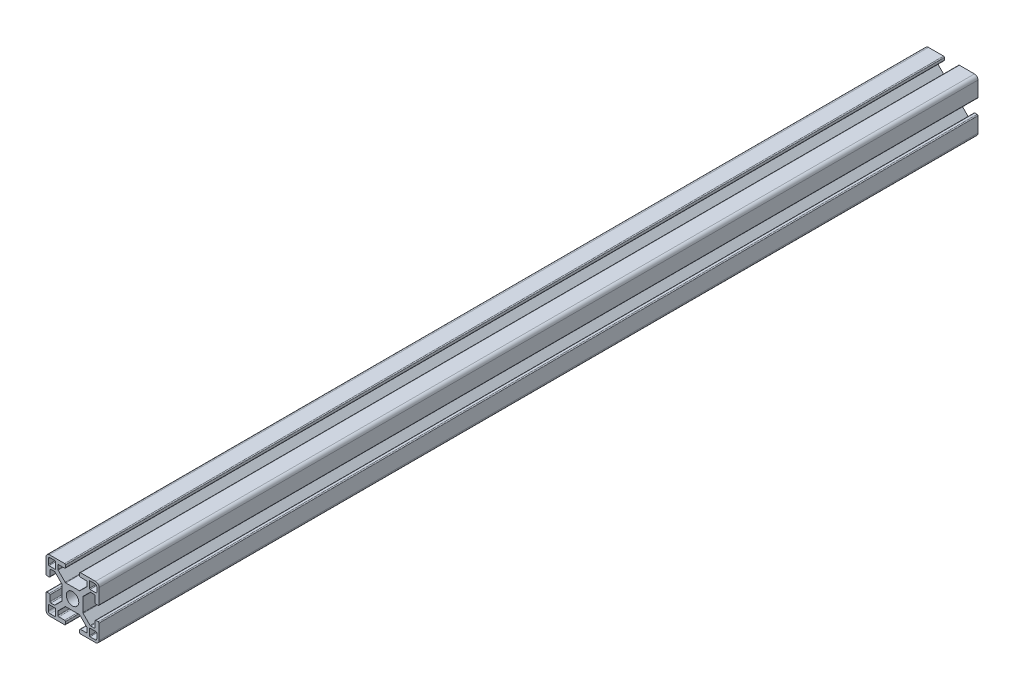
SolidWorks part; units mm, degrees
ref_plane "Front Plane" through (0, 0, 0) normal (0, 0, 1) x (1, 0, 0)
ref_plane "Top Plane" through (0, 0, 0) normal (0, 1, 0) x (1, 0, 0)
ref_plane "Right Plane" through (0, 0, 0) normal (1, 0, 0) x (0, 0, -1)
sketch "Sketch1" plane through (0, 0, 0) normal (0, 0, 1) x (1, 0, 0)
  line L0 (3.9799, -2.4733) -> (3.1981, -1.4942) construction
  line L1 (1.4942, -3.1981) -> (2.4733, -3.9799) construction
  line L2 (-2.4733, -3.9799) -> (-1.4942, -3.1981) construction
  line L3 (-3.1981, -1.4942) -> (-3.9799, -2.4733) construction
  line L4 (-3.9799, 2.4733) -> (-3.1981, 1.4942) construction
  line L5 (-1.4942, 3.1981) -> (-2.4733, 3.9799) construction
  line L6 (2.4733, 3.9799) -> (1.4942, 3.1981) construction
  line L7 (3.1981, 1.4942) -> (3.9799, 2.4733) construction
  line L8 (-12.6999, -13.6999) -> (-9.881, -13.6999)
  line L9 (-13.6999, -9.881) -> (-13.6999, -12.6999)
  line L10 (-9.88, -9.5) -> (-13.3189, -9.5)
  line L11 (-9.5, -13.3189) -> (-9.5, -9.88)
  line L12 (13.6999, -12.6999) -> (13.6999, -9.881)
  line L13 (9.881, -13.6999) -> (12.6999, -13.6999)
  line L14 (9.5, -9.88) -> (9.5, -13.3189)
  line L15 (13.3189, -9.5) -> (9.88, -9.5)
  line L16 (9.88, 9.5) -> (13.3189, 9.5)
  line L17 (9.5, 13.3189) -> (9.5, 9.88)
  line L18 (12.6999, 13.6999) -> (9.881, 13.6999)
  line L19 (13.6999, 9.881) -> (13.6999, 12.6999)
  line L20 (-13.6999, 12.6999) -> (-13.6999, 9.881)
  line L21 (-9.881, 13.6999) -> (-12.6999, 13.6999)
  line L22 (-9.5, 9.88) -> (-9.5, 13.3189)
  line L23 (-13.3189, 9.5) -> (-9.88, 9.5)
  line L24 (14.4999, -4) -> (13.2425, -4)
  line L25 (12.7425, -4.5) -> (12.7425, -7.7325)
  line L26 (12.2428, -8.25) -> (10.2602, -8.25)
  line L27 (9.9066, -8.1035) -> (5.9811, -4.178)
  line L28 (5.8347, -3.8245) -> (5.8347, -1.0125)
  line L29 (5.8347, -1.0125) -> (5.3247, -0.0625) construction
  line L30 (5.3247, -0.0625) -> (5.8347, 0.8875) construction
  line L31 (5.8347, 0.8875) -> (5.8347, 3.8245)
  line L32 (5.9811, 4.178) -> (9.9066, 8.1035)
  line L33 (10.2602, 8.25) -> (12.2428, 8.25)
  line L34 (12.7425, 7.7325) -> (12.7425, 4.5)
  line L35 (13.2425, 4) -> (14.4999, 4)
  line L36 (14.9999, 4.5) -> (14.9999, 12.9999)
  line L37 (12.9999, 14.9999) -> (4.5, 14.9999)
  line L38 (4, 14.4999) -> (4, 13.2425)
  line L39 (4.5, 12.7425) -> (7.7325, 12.7425)
  line L40 (8.25, 12.2428) -> (8.25, 10.2602)
  line L41 (8.1035, 9.9066) -> (4.178, 5.9811)
  line L42 (3.8245, 5.8347) -> (0.95, 5.8347)
  line L43 (0.95, 5.8347) -> (0, 5.3247) construction
  line L44 (0, 5.3247) -> (-0.95, 5.8347) construction
  line L45 (-0.95, 5.8347) -> (-3.8245, 5.8347)
  line L46 (-4.178, 5.9811) -> (-8.1035, 9.9066)
  line L47 (-8.25, 10.2602) -> (-8.25, 12.2428)
  line L48 (-7.7325, 12.7425) -> (-4.5, 12.7425)
  line L49 (-4, 13.2425) -> (-4, 14.4999)
  line L50 (-4.5, 14.9999) -> (-12.9999, 14.9999)
  line L51 (-14.9999, 12.9999) -> (-14.9999, 4.5)
  line L52 (-14.4999, 4) -> (-13.2425, 4)
  line L53 (-12.7425, 4.5) -> (-12.7425, 7.7325)
  line L54 (-12.2428, 8.25) -> (-10.2602, 8.25)
  line L55 (-9.9066, 8.1035) -> (-5.9811, 4.178)
  line L56 (-5.8347, 3.8245) -> (-5.8347, 0.8875)
  line L57 (-5.8347, 0.8875) -> (-5.3247, -0.0625) construction
  line L58 (-5.3247, -0.0625) -> (-5.8347, -1.0125) construction
  line L59 (-5.8347, -1.0125) -> (-5.8347, -3.8245)
  line L60 (-5.9811, -4.178) -> (-9.9066, -8.1035)
  line L61 (-10.2602, -8.25) -> (-12.2428, -8.25)
  line L62 (-12.7425, -7.7325) -> (-12.7425, -4.5)
  line L63 (-13.2425, -4) -> (-14.4999, -4)
  line L64 (-14.9999, -4.5) -> (-14.9999, -12.9999)
  line L65 (-12.9999, -14.9999) -> (-4.5, -14.9999)
  line L66 (-4, -14.4999) -> (-4, -13.2425)
  line L67 (-4.5, -12.7425) -> (-7.7325, -12.7425)
  line L68 (-8.25, -12.2428) -> (-8.25, -10.2602)
  line L69 (-8.1035, -9.9066) -> (-4.178, -5.9811)
  line L70 (-3.8245, -5.8347) -> (-0.95, -5.8347)
  line L71 (-0.95, -5.8347) -> (0, -5.3247) construction
  line L72 (0, -5.3247) -> (0.95, -5.8347) construction
  line L73 (0.95, -5.8347) -> (3.8245, -5.8347)
  line L74 (4.178, -5.9811) -> (8.1035, -9.9066)
  line L75 (8.25, -10.2602) -> (8.25, -12.2428)
  line L76 (7.7325, -12.7425) -> (4.5, -12.7425)
  line L77 (4, -13.2425) -> (4, -14.4999)
  line L78 (4.5, -14.9999) -> (12.9999, -14.9999)
  line L79 (14.9999, -12.9999) -> (14.9999, -4.5)
  line L80 (-5.8347, -1.0125) -> (-5.8347, 0.8875)
  line L81 (-0.95, 5.8347) -> (0.95, 5.8347)
  line L82 (5.8347, 0.8875) -> (5.8347, -1.0125)
  line L83 (-0.95, -5.8347) -> (0.95, -5.8347)
  arc A0 (2.4733, -3.9799) -> (3.9799, -2.4733) centre (3.1422, -3.1422) ccw construction
  arc A1 (-1.4942, -3.1981) -> (1.4942, -3.1981) centre (0, 0) ccw construction
  arc A2 (-3.9799, -2.4733) -> (-2.4733, -3.9799) centre (-3.1422, -3.1422) ccw construction
  arc A3 (-3.1981, 1.4942) -> (-3.1981, -1.4942) centre (0, 0) ccw construction
  arc A4 (-2.4733, 3.9799) -> (-3.9799, 2.4733) centre (-3.1422, 3.1422) ccw construction
  arc A5 (1.4942, 3.1981) -> (-1.4942, 3.1981) centre (0, 0) ccw construction
  arc A6 (3.9799, 2.4733) -> (2.4733, 3.9799) centre (3.1422, 3.1422) ccw construction
  arc A7 (3.1981, -1.4942) -> (3.1981, 1.4942) centre (0, 0) ccw construction
  arc A8 (-13.6999, -12.6999) -> (-12.6999, -13.6999) centre (-12.6999, -12.6999) ccw
  arc A9 (-13.3189, -9.5) -> (-13.6999, -9.881) centre (-13.3189, -9.881) ccw
  arc A10 (-9.5, -9.88) -> (-9.88, -9.5) centre (-9.88, -9.88) ccw
  arc A11 (-9.881, -13.6999) -> (-9.5, -13.3189) centre (-9.881, -13.3189) ccw
  arc A12 (12.6999, -13.6999) -> (13.6999, -12.6999) centre (12.6999, -12.6999) ccw
  arc A13 (9.5, -13.3189) -> (9.881, -13.6999) centre (9.881, -13.3189) ccw
  arc A14 (9.88, -9.5) -> (9.5, -9.88) centre (9.88, -9.88) ccw
  arc A15 (13.6999, -9.881) -> (13.3189, -9.5) centre (13.3189, -9.881) ccw
  arc A16 (9.5, 9.88) -> (9.88, 9.5) centre (9.88, 9.88) ccw
  arc A17 (9.881, 13.6999) -> (9.5, 13.3189) centre (9.881, 13.3189) ccw
  arc A18 (13.6999, 12.6999) -> (12.6999, 13.6999) centre (12.6999, 12.6999) ccw
  arc A19 (13.3189, 9.5) -> (13.6999, 9.881) centre (13.3189, 9.881) ccw
  arc A20 (14.9999, -4.5) -> (14.4999, -4) centre (14.4999, -4.5) ccw
  arc A21 (13.2425, -4) -> (12.7425, -4.5) centre (13.2425, -4.5) ccw
  arc A22 (12.2428, -8.25) -> (12.7425, -7.7325) centre (12.2428, -7.75) ccw
  arc A23 (9.9066, -8.1035) -> (10.2602, -8.25) centre (10.2602, -7.75) ccw
  arc A24 (5.8347, -3.8245) -> (5.9811, -4.178) centre (6.3347, -3.8245) ccw
  arc A25 (5.9811, 4.178) -> (5.8347, 3.8245) centre (6.3347, 3.8245) ccw
  arc A26 (10.2602, 8.25) -> (9.9066, 8.1035) centre (10.2602, 7.75) ccw
  arc A27 (12.7425, 7.7325) -> (12.2428, 8.25) centre (12.2428, 7.75) ccw
  arc A28 (12.7425, 4.5) -> (13.2425, 4) centre (13.2425, 4.5) ccw
  arc A29 (14.4999, 4) -> (14.9999, 4.5) centre (14.4999, 4.5) ccw
  arc A30 (14.9999, 12.9999) -> (12.9999, 14.9999) centre (12.9999, 12.9999) ccw
  arc A31 (4.5, 14.9999) -> (4, 14.4999) centre (4.5, 14.4999) ccw
  arc A32 (4, 13.2425) -> (4.5, 12.7425) centre (4.5, 13.2425) ccw
  arc A33 (8.25, 12.2428) -> (7.7325, 12.7425) centre (7.75, 12.2428) ccw
  arc A34 (8.1035, 9.9066) -> (8.25, 10.2602) centre (7.75, 10.2602) ccw
  arc A35 (3.8245, 5.8347) -> (4.178, 5.9811) centre (3.8245, 6.3347) ccw
  arc A36 (-4.178, 5.9811) -> (-3.8245, 5.8347) centre (-3.8245, 6.3347) ccw
  arc A37 (-8.25, 10.2602) -> (-8.1035, 9.9066) centre (-7.75, 10.2602) ccw
  arc A38 (-7.7325, 12.7425) -> (-8.25, 12.2428) centre (-7.75, 12.2428) ccw
  arc A39 (-4.5, 12.7425) -> (-4, 13.2425) centre (-4.5, 13.2425) ccw
  arc A40 (-4, 14.4999) -> (-4.5, 14.9999) centre (-4.5, 14.4999) ccw
  arc A41 (-12.9999, 14.9999) -> (-14.9999, 12.9999) centre (-12.9999, 12.9999) ccw
  arc A42 (-14.9999, 4.5) -> (-14.4999, 4) centre (-14.4999, 4.5) ccw
  arc A43 (-13.2425, 4) -> (-12.7425, 4.5) centre (-13.2425, 4.5) ccw
  arc A44 (-12.2428, 8.25) -> (-12.7425, 7.7325) centre (-12.2428, 7.75) ccw
  arc A45 (-9.9066, 8.1035) -> (-10.2602, 8.25) centre (-10.2602, 7.75) ccw
  arc A46 (-5.8347, 3.8245) -> (-5.9811, 4.178) centre (-6.3347, 3.8245) ccw
  arc A47 (-5.9811, -4.178) -> (-5.8347, -3.8245) centre (-6.3347, -3.8245) ccw
  arc A48 (-10.2602, -8.25) -> (-9.9066, -8.1035) centre (-10.2602, -7.75) ccw
  arc A49 (-12.7425, -7.7325) -> (-12.2428, -8.25) centre (-12.2428, -7.75) ccw
  arc A50 (-12.7425, -4.5) -> (-13.2425, -4) centre (-13.2425, -4.5) ccw
  arc A51 (-14.4999, -4) -> (-14.9999, -4.5) centre (-14.4999, -4.5) ccw
  arc A52 (-14.9999, -12.9999) -> (-12.9999, -14.9999) centre (-12.9999, -12.9999) ccw
  arc A53 (-4.5, -14.9999) -> (-4, -14.4999) centre (-4.5, -14.4999) ccw
  arc A54 (-4, -13.2425) -> (-4.5, -12.7425) centre (-4.5, -13.2425) ccw
  arc A55 (-8.25, -12.2428) -> (-7.7325, -12.7425) centre (-7.75, -12.2428) ccw
  arc A56 (-8.1035, -9.9066) -> (-8.25, -10.2602) centre (-7.75, -10.2602) ccw
  arc A57 (-3.8245, -5.8347) -> (-4.178, -5.9811) centre (-3.8245, -6.3347) ccw
  arc A58 (4.178, -5.9811) -> (3.8245, -5.8347) centre (3.8245, -6.3347) ccw
  arc A59 (8.25, -10.2602) -> (8.1035, -9.9066) centre (7.75, -10.2602) ccw
  arc A60 (7.7325, -12.7425) -> (8.25, -12.2428) centre (7.75, -12.2428) ccw
  arc A61 (4.5, -12.7425) -> (4, -13.2425) centre (4.5, -13.2425) ccw
  arc A62 (4, -14.4999) -> (4.5, -14.9999) centre (4.5, -14.4999) ccw
  arc A63 (12.9999, -14.9999) -> (14.9999, -12.9999) centre (12.9999, -12.9999) ccw
  arc A64 (-12.6999, 13.6999) -> (-13.6999, 12.6999) centre (-12.6999, 12.6999) ccw
  arc A65 (-9.5, 13.3189) -> (-9.881, 13.6999) centre (-9.881, 13.3189) ccw
  arc A66 (-9.88, 9.5) -> (-9.5, 9.88) centre (-9.88, 9.88) ccw
  arc A67 (-13.6999, 9.881) -> (-13.3189, 9.5) centre (-13.3189, 9.881) ccw
  circle A68 centre (0, 0) radius 3.53
extrude "Boss-Extrude1" add sketch "Sketch1" along normal mid plane 496.9
